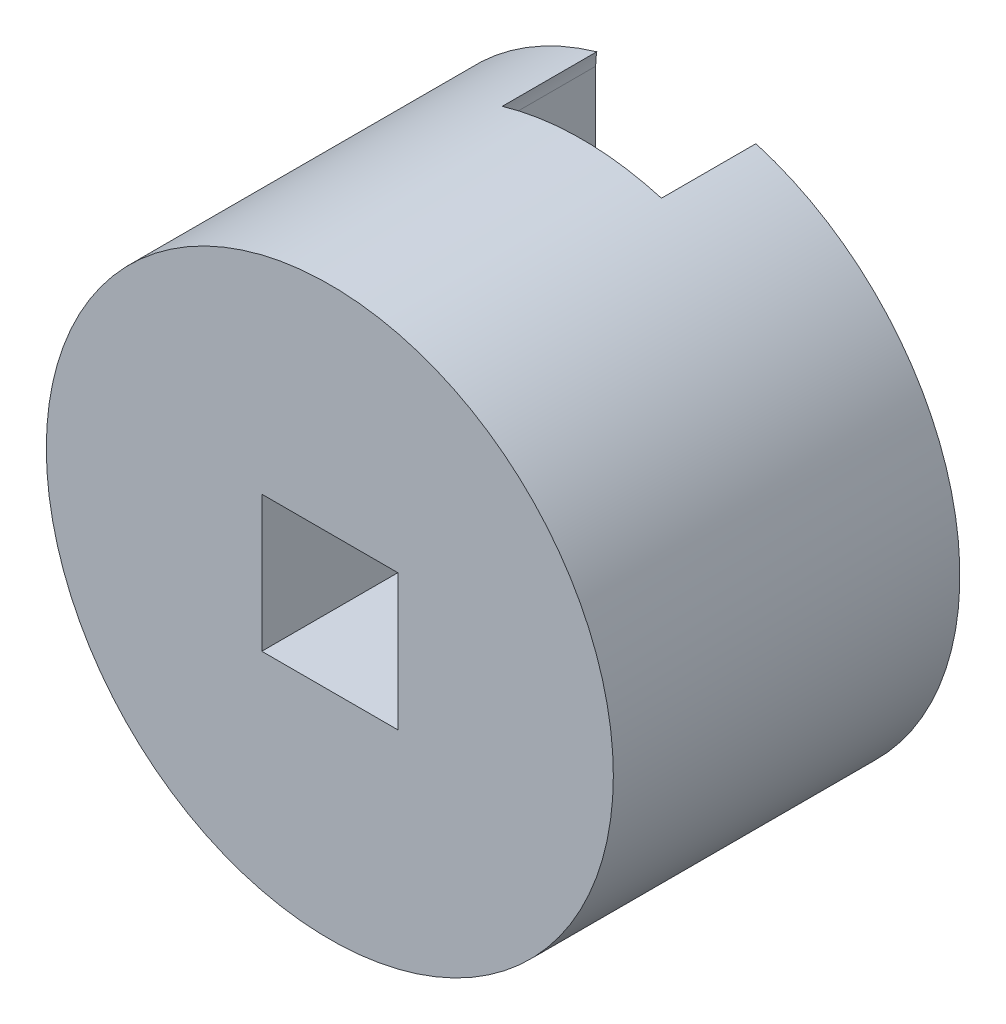
SolidWorks part; units mm, degrees
ref_plane "Front Plane" through (0, 0, 0) normal (0, 0, 1) x (1, 0, 0)
ref_plane "Top Plane" through (0, 0, 0) normal (0, 1, 0) x (1, 0, 0)
ref_plane "Right Plane" through (0, 0, 0) normal (1, 0, 0) x (0, 0, -1)
sketch "Sketch1" plane through (0, 0, 20.1102) normal (0, 0, 1) x (1, 0, 0)
  line L4 (0, 13.6525) -> (0, 14.4463) construction
  line L8 (-2.032, 2.0884) -> (-2.032, -1.4351)
  line L9 (2.032, -1.4351) -> (2.032, 2.0884)
  line L10 (2.032, 8.097) -> (2.032, 11.6205)
  line L11 (-2.032, 11.6205) -> (-2.032, 8.097)
  line L12 (-2.032, 2.0884) -> (-2.032, -1.4351)
  line L13 (2.032, -1.4351) -> (2.032, 2.0884)
  line L14 (2.032, 8.097) -> (2.032, 11.6205)
  line L15 (-2.032, 11.6205) -> (-2.032, 8.097)
  circle A4 centre (0, 5.0927) radius 9.3536
  arc A8 (-2.032, 8.097) -> (-2.032, 2.0884) centre (0, 5.0927) ccw
  arc A9 (-2.032, -1.4351) -> (2.032, -1.4351) centre (0, -1.4351) ccw
  arc A10 (2.032, 2.0884) -> (2.032, 8.097) centre (0, 5.0927) ccw
  arc A11 (2.032, 11.6205) -> (-2.032, 11.6205) centre (0, 11.6205) ccw
  arc A12 (-2.032, 8.097) -> (-2.032, 2.0884) centre (0, 5.0927) ccw
  arc A13 (-2.032, -1.4351) -> (2.032, -1.4351) centre (0, -1.4351) ccw
  arc A14 (2.032, 2.0884) -> (2.032, 8.097) centre (0, 5.0927) ccw
  arc A15 (2.032, 11.6205) -> (-2.032, 11.6205) centre (0, 11.6205) ccw
  dimension "D2" = 0.7937
  dimension "D1" = 0.127
extrude "Boss-Extrude1" add sketch "Sketch1" against normal blind 2.3813
sketch "Sketch2" plane through (0, 0, 20.1102) normal (0, 0, 1) x (1, 0, 0)
  line L8 (1.7145, 3.3782) -> (1.7145, 6.8072)
  line L9 (1.7145, 6.8072) -> (-1.7145, 6.8072)
  line L10 (-1.7145, 6.8072) -> (-1.7145, 3.3782)
  line L11 (-1.7145, 3.3782) -> (1.7145, 3.3782)
  line L12 (1.7145, 3.3782) -> (1.7145, 6.8072)
  line L13 (1.7145, 6.8072) -> (-1.7145, 6.8072)
  line L14 (-1.7145, 6.8072) -> (-1.7145, 3.3782)
  line L15 (-1.7145, 3.3782) -> (1.7145, 3.3782)
  circle A1 centre (0, 5.0927) radius 9.3536
  circle A2 centre (0, 5.0927) radius 9.3536
  dimension "D1" = 0
  dimension "D2" = 0.127
extrude "Boss-Extrude2" add sketch "Sketch2" along normal blind 6.35
sketch "Sketch3" plane through (0, 0, 20.1102) normal (0, 0, -1) x (-1, 0, 0)
  line L0 (-1.7145, 6.8072) -> (1.7145, 3.3782) construction
  line L4 (-1.7145, 3.3782) -> (1.7145, 3.3782)
  line L5 (-1.7145, 6.8072) -> (-1.7145, 3.3782)
  line L6 (1.7145, 6.8072) -> (-1.7145, 6.8072)
  line L7 (1.7145, 3.3782) -> (1.7145, 6.8072)
  line L8 (-1.7145, 3.3782) -> (1.7145, 3.3782)
  line L9 (-1.7145, 6.8072) -> (-1.7145, 3.3782)
  line L10 (1.7145, 6.8072) -> (-1.7145, 6.8072)
  line L11 (1.7145, 3.3782) -> (1.7145, 6.8072)
  circle A0 centre (0, 5.0927) radius 1.25
  dimension "D2" = 2.5
  dimension "D1" = 0
extrude "Boss-Extrude3" add sketch "Sketch3" against normal blind 1
sketch "Sketch4" plane through (0, 0, 17.7289) normal (0, 0, -1) x (-1, 0, 0)
  circle A0 centre (0, 5.0927) radius 7.1438
  dimension "D1" = 14.2875
extrude "Cut-Extrude1" cut sketch "Sketch4" against normal through all both and the other way through all flip side to cut
